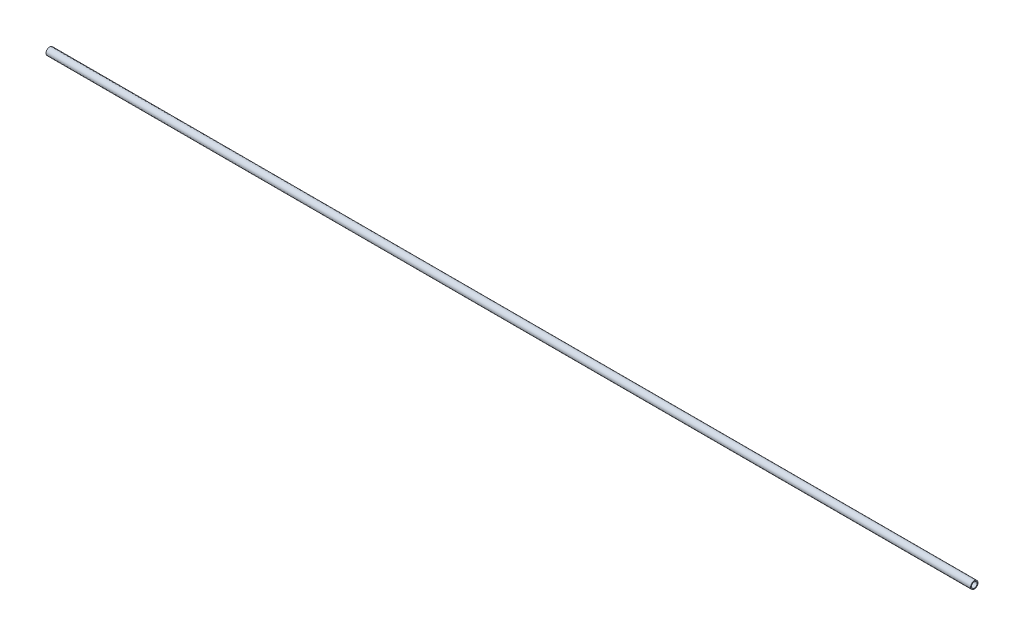
SolidWorks part; units mm, degrees
ref_plane "Plano frontal" through (0, 0, 0) normal (0, 0, 1) x (1, 0, 0)
ref_plane "Plano superior" through (0, 0, 0) normal (0, 1, 0) x (1, 0, 0)
ref_plane "Plano direito" through (0, 0, 0) normal (1, 0, 0) x (0, 0, -1)
sketch "Esboço1" plane through (0, 0, 0) normal (1, 0, 0) x (0, 0, -1)
  circle A0 centre (0, 0) radius 2
  circle A1 centre (0, 0) radius 1.5
extrude "Ressalto-extrusão1" add sketch "Esboço1" along normal blind 501
